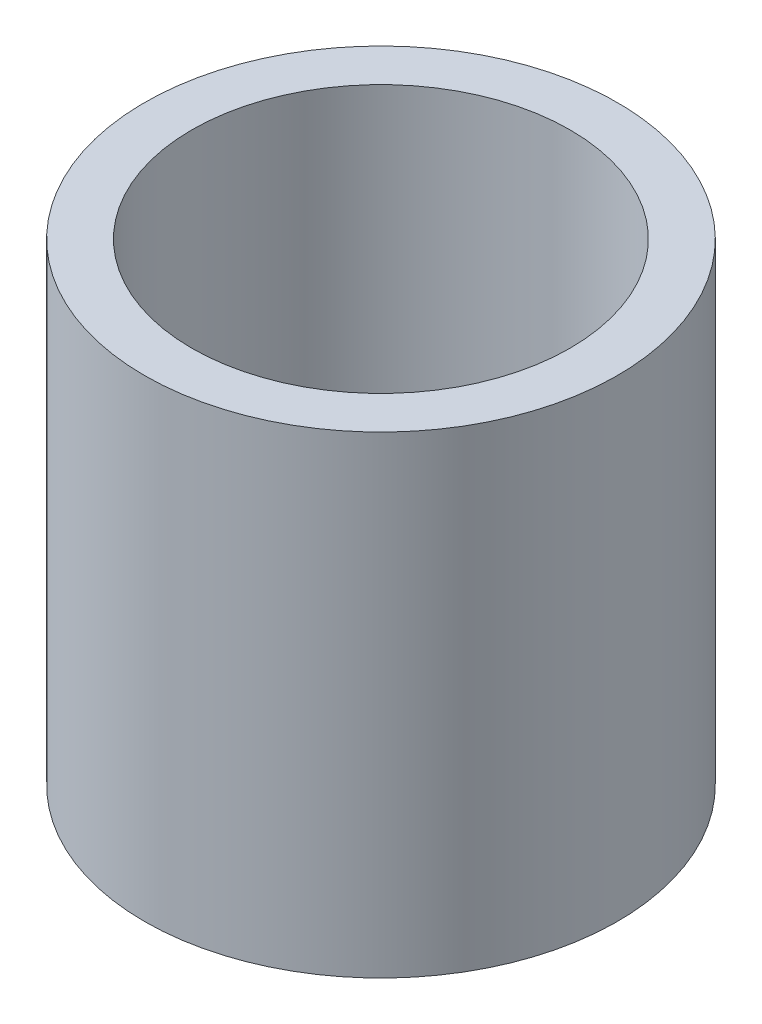
SolidWorks part; units mm, degrees
ref_plane "Front Plane" through (0, 0, 0) normal (0, 0, 1) x (1, 0, 0)
ref_plane "Top Plane" through (0, 0, 0) normal (0, 1, 0) x (1, 0, 0)
ref_plane "Right Plane" through (0, 0, 0) normal (1, 0, 0) x (0, 0, -1)
sketch "Sketch1" plane through (0, 0, 0) normal (0, 1, 0) x (1, 0, 0)
  circle A0 centre (0, 0) radius 4
  circle A1 centre (0, 0) radius 5
  dimension "D1" = 8
  dimension "D2" = 10
extrude "Boss-Extrude1" add sketch "Sketch1" along normal blind 10
